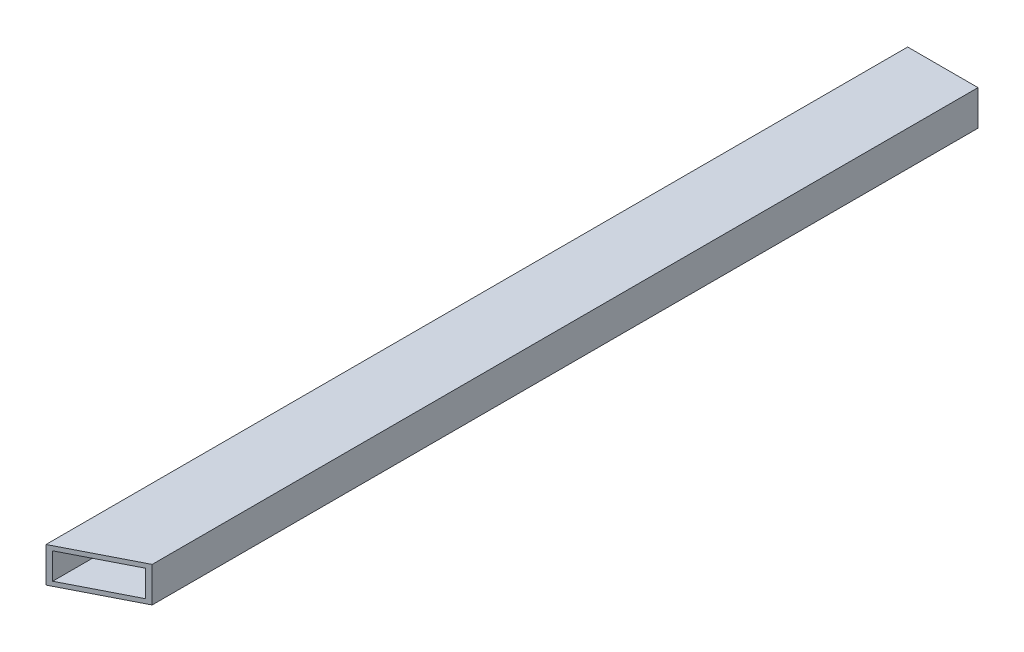
SolidWorks part; units mm, degrees
ref_plane "Front Plane" through (0, 0, 0) normal (0, 0, 1) x (1, 0, 0)
ref_plane "Top Plane" through (0, 0, 0) normal (0, 1, 0) x (1, 0, 0)
ref_plane "Right Plane" through (0, 0, 0) normal (1, 0, 0) x (0, 0, -1)
sketch "Sketch2" plane through (0, 0, 0) normal (0, 0, 1) x (1, 0, 0)
  line L1 (-25.4, -12.7) -> (25.4, -12.7)
  line L2 (-25.4, -12.7) -> (-25.4, 12.7)
  line L3 (-25.4, 12.7) -> (25.4, 12.7)
  line L4 (25.4, -12.7) -> (25.4, 12.7)
  line L5 (-25.4, -12.7) -> (25.4, 12.7) construction
  line L6 (-25.4, 12.7) -> (25.4, -12.7) construction
  line L7 (-22.225, -9.525) -> (22.225, -9.525)
  line L8 (-22.225, -9.525) -> (-22.225, 9.525)
  line L9 (-22.225, 9.525) -> (22.225, 9.525)
  line L10 (22.225, -9.525) -> (22.225, 9.525)
  line L11 (-22.225, -9.525) -> (22.225, 9.525) construction
  line L12 (-22.225, 9.525) -> (22.225, -9.525) construction
  point P0 (0, 0)
  point P6 (0, 0)
  dimension "D1" = 50.8
  dimension "D2" = 25.4
  dimension "D3" = 44.45
  dimension "D4" = 19.05
extrude "Boss-Extrude1" add sketch "Sketch2" along normal blind 622.3
sketch "Sketch3" plane through (0, 12.7, 0) normal (0, 1, 0) x (1, 0, 0)
  line L0 (-25.4, -622.3) -> (25.4, -596.4161)
  line L1 (25.4, -622.3) -> (25.4, 0) construction
  line L2 (-25.4, -622.3) -> (-25.4, 0) construction
  line L3 (-25.4, -622.3) -> (25.4, -622.3)
  line L4 (25.4, -622.3) -> (-25.4, -622.3) construction
  line L5 (25.4, -622.3) -> (25.4, -596.4161)
  dimension "D1" = 63
extrude "Cut-Extrude1" cut sketch "Sketch3" against normal up to surface (25.4 mm away) up to face at (0, -12.7, 311.15)
